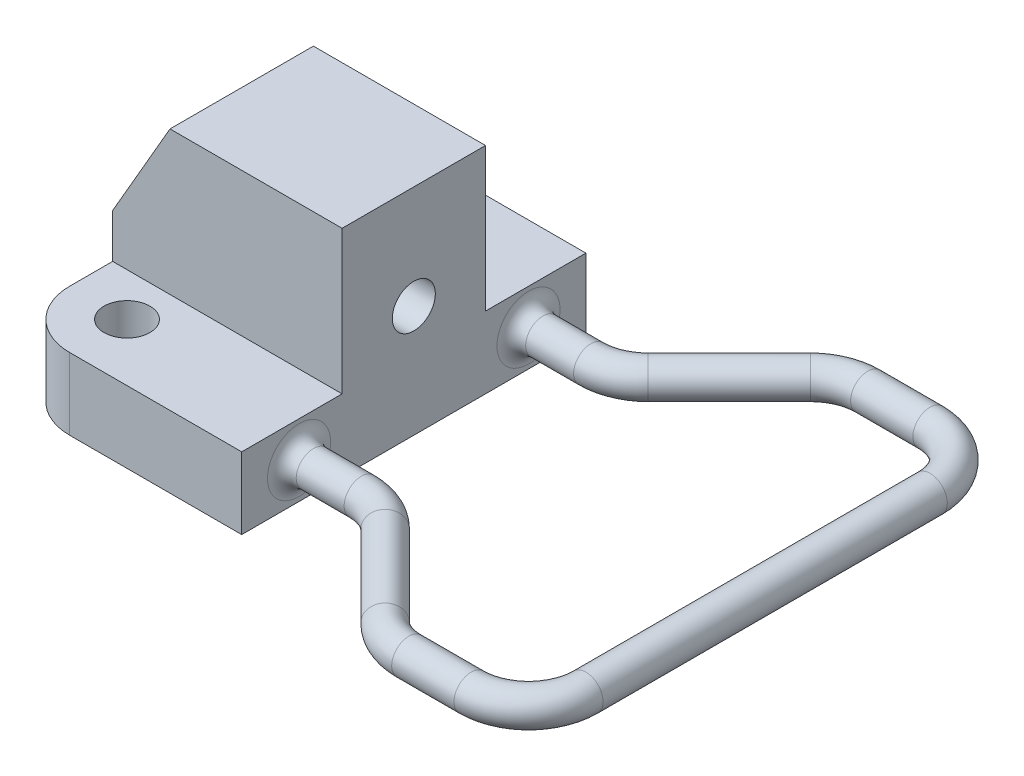
SolidWorks part; units mm, degrees
ref_plane "前视基准面" through (0, 0, 0) normal (0, 0, 1) x (1, 0, 0)
ref_plane "上视基准面" through (0, 0, 0) normal (0, 1, 0) x (1, 0, 0)
ref_plane "右视基准面" through (0, 0, 0) normal (1, 0, 0) x (0, 0, -1)
other "Configuration Table"
sketch "草图1" plane through (0, 0, 0) normal (0, 1, 0) x (1, 0, 0)
  line L1 (-20, 60) -> (40, 60)
  line L2 (-40, 40) -> (-40, -40)
  line L3 (-20, -60) -> (40, -60)
  line L4 (40, 60) -> (40, -60)
  line L5 (-40, 60) -> (40, -60) construction
  line L6 (-40, -60) -> (40, 60) construction
  arc A0 (-40, -40) -> (-20, -60) centre (-20, -40) ccw
  arc A1 (-20, 60) -> (-40, 40) centre (-20, 40) ccw
  circle A2 centre (-20, -40) radius 8
  circle A3 centre (-20, 40) radius 8
  point P0 (0, 0)
  dimension "D3" = 20
  dimension "D4" = 16
  dimension "D1" = 80
  dimension "D2" = 120
extrude "凸台-拉伸1" add sketch "草图1" along normal blind 25
sketch "草图2" plane through (0, 0, 0) normal (0, 0, 1) x (1, 0, 0)
  line L0 (40, 25) -> (-40, 25)
  line L1 (-40, 25) -> (-40, 40.359)
  line L2 (-40, 40.359) -> (-20, 75)
  line L3 (-20, 75) -> (40, 75)
  line L4 (40, 75) -> (40, 25)
  dimension "D1" = 50
  dimension "D2" = 30
  dimension "D3" = 20
extrude "凸台-拉伸2" add sketch "草图2" along normal mid plane 50 contours L4 L0 L1 L2 L3
sketch "草图4" plane through (0, 0, 0) normal (0, 0, 1) x (1, 0, 0)
  line L0 (-26.25, 64.1747) -> (-0.8577, 49.5144)
  line L1 (-40, 40.359) -> (-20, 75) construction
  line L2 (14.1423, 45.4952) -> (40, 45.4952)
  line L3 (40, 75) -> (40, 25) construction
  line L4 (-30, 57.6795) -> (-14.1925, 48.553)
  line L5 (-33.75, 51.1843) -> (-8.3577, 36.524)
  line L6 (6.6423, 32.5048) -> (40, 32.5048)
  line L7 (40, 32.5048) -> (40, 45.4952)
  line L8 (40, 39) -> (21.3383, 39)
  line L9 (-20, 75) -> (40, 75) construction
  line L10 (-14.1925, 48.553) -> (-4.6077, 43.0192)
  line L11 (10.3923, 39) -> (21.3383, 39)
  arc A0 (-8.3577, 36.524) -> (6.6423, 32.5048) centre (6.6423, 62.5048) ccw
  arc A1 (-0.8577, 49.5144) -> (14.1423, 45.4952) centre (14.1423, 75.4952) ccw
  arc A2 (-4.6077, 43.0192) -> (10.3923, 39) centre (10.3923, 69) ccw
  point P14 (-1.3962, 32.5048)
  point P17 (6.1038, 45.4952)
  dimension "D2" = 30
  dimension "D4" = 30
  dimension "D1" = 7.5
  dimension "D3" = 36
sketch "草图11" plane through (-47.476, 27.4103, 0) normal (-0.866, 0.5, 0) x (0, 0, 1)
  circle A0 centre (0, 34.9519) radius 7.5
  dimension "D1" = 15
sweep "切除-扫描2" cut profiles "草图11" path "草图4"
sketch "草图12" plane through (40, 0, 0) normal (1, 0, 0) x (0, 0, -1)
  line L0 (60, 12.5) -> (-63.8202, 12.5) construction
  line L1 (60, 25) -> (60, 0) construction
ref_plane "基准面1" through (0, 12.5, 0) normal (0, 1, 0) x (0, 0, 1)
sketch "草图13" plane through (0, 12.5, 0) normal (0, 1, 0) x (0, 0, 1)
  line L0 (-40, -20) -> (-40, 40) construction
  line L1 (-60, 40) -> (63.8202, 40) construction
  line L2 (-40, 40) -> (-40, 61.7157)
  line L3 (-45.8579, 75.8579) -> (-74.1421, 104.1421)
  line L4 (-80, 118.2843) -> (-80, 140)
  line L5 (-60, 160) -> (60, 160)
  line L6 (0, 0) -> (0, 96.7824) construction
  line L7 (80, 118.2843) -> (80, 140)
  line L8 (45.8579, 75.8579) -> (74.1421, 104.1421)
  line L9 (40, 40) -> (40, 61.7157)
  arc A0 (45.8579, 75.8579) -> (40, 61.7157) centre (60, 61.7157) ccw
  arc A1 (80, 140) -> (60, 160) centre (60, 140) ccw
  arc A2 (80, 118.2843) -> (74.1421, 104.1421) centre (60, 118.2843) cw
  arc A3 (-80, 140) -> (-60, 160) centre (-60, 140) cw
  arc A4 (-74.1421, 104.1421) -> (-80, 118.2843) centre (-60, 118.2843) cw
  arc A5 (-40, 61.7157) -> (-45.8579, 75.8579) centre (-60, 61.7157) ccw
  point P18 (40, 70)
  point P21 (80, 160)
  point P24 (80, 110)
  point P27 (-80, 160)
  point P30 (-80, 110)
  point P33 (-40, 70)
  dimension "D5" = 20
  dimension "D1" = 45
  dimension "D2" = 30
  dimension "D3" = 160
  dimension "D4" = 120
sweep "扫描1" add path "草图13" circular profile diameter 12 parameters "D3"=12
fillet "圆角1" radius 5 2 edges at (40, 12.5, 34) (40, 12.5, -34)
